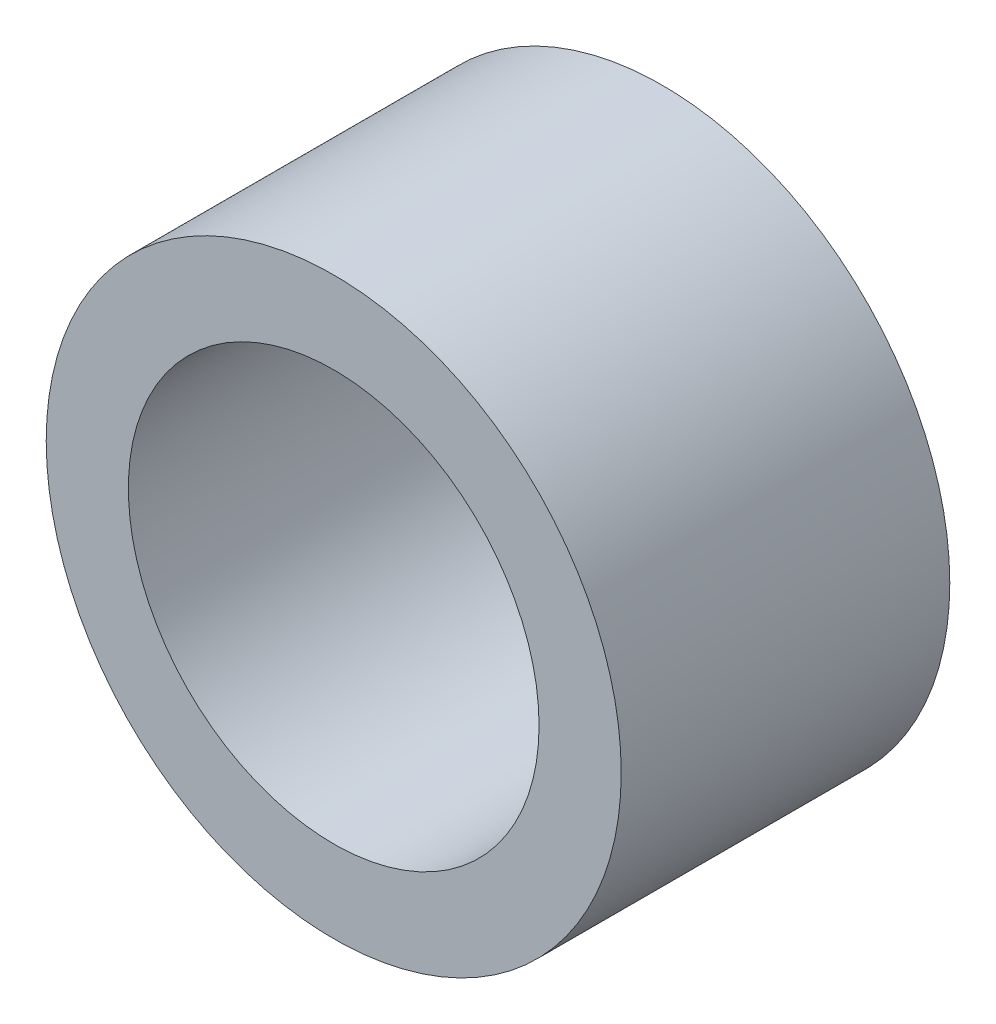
SolidWorks part; units mm, degrees
ref_plane "Front Plane" through (0, 0, 0) normal (0, 0, 1) x (1, 0, 0)
ref_plane "Top Plane" through (0, 0, 0) normal (0, 1, 0) x (1, 0, 0)
ref_plane "Right Plane" through (0, 0, 0) normal (1, 0, 0) x (0, 0, -1)
sketch "Sketch1" plane through (0, 0, 0) normal (0, 0, 1) x (1, 0, 0)
  circle A0 centre (0, 0) radius 31.75
  circle A1 centre (0, 0) radius 44.45
  dimension "D1" = 63.5
  dimension "D2" = 88.9
extrude "Boss-Extrude1" add sketch "Sketch1" against normal blind 50.8 from offset 25.4
